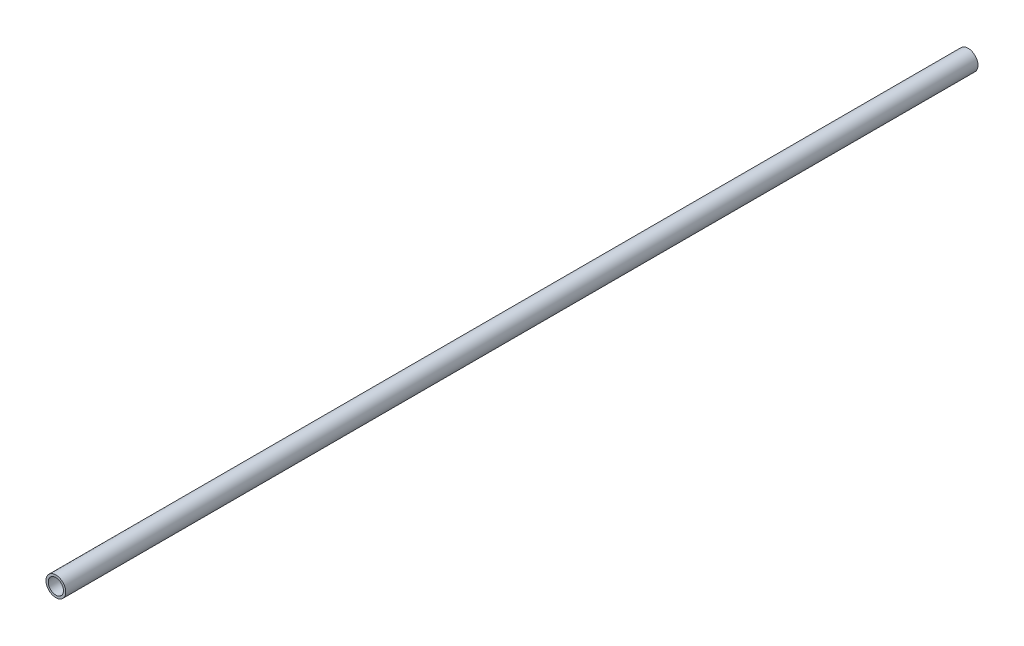
SolidWorks part; units mm, degrees
material "ABS PC"
ref_plane "Alzado" through (0, 0, 0) normal (1, 0, 0) x (0, 1, 0)
ref_plane "Planta" through (0, 0, 0) normal (0, 0, 1) x (0, 1, 0)
ref_plane "Vista lateral" through (0, 0, 0) normal (0, 1, 0) x (-1, 0, 0)
sketch "Croquis2" plane through (0, 0, 0) normal (0, 0, 1) x (0, 1, 0)
  circle A0 centre (0, 0) radius 6.5
  circle A1 centre (0, 0) radius 5
  dimension "D1" = 13
  dimension "D2" = 10
extrude "Saliente-Extruir1" add sketch "Croquis2" along normal blind 600
